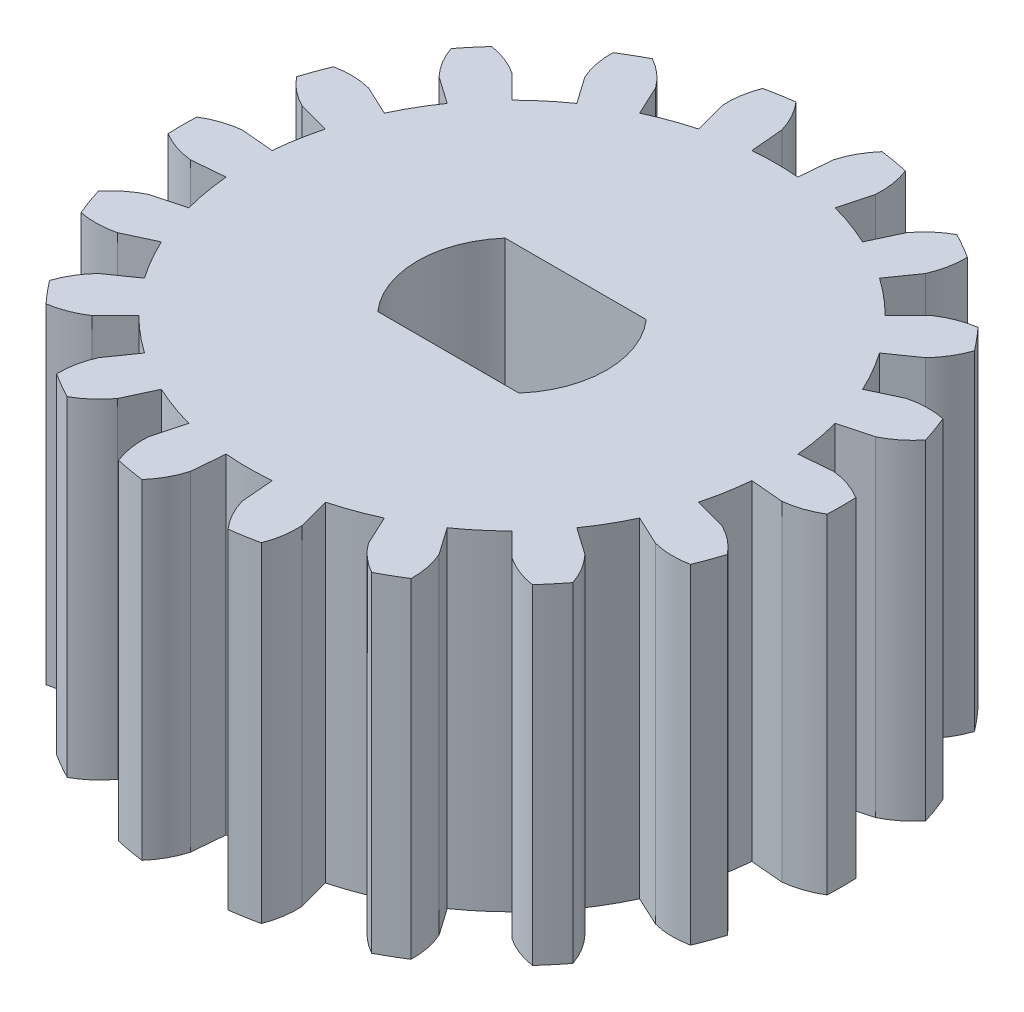
SolidWorks part; units mm, degrees
ref_plane "Front Plane" through (0, 0, 0) normal (0, 0, 1) x (1, 0, 0)
ref_plane "Top Plane" through (0, 0, 0) normal (0, 1, 0) x (1, 0, 0)
ref_plane "Right Plane" through (0, 0, 0) normal (1, 0, 0) x (0, 0, -1)
sketch "Sketch1" plane through (0, 0, 0) normal (0, 1, 0) x (1, 0, 0)
  line L0 (0, 0) -> (11.1857, 0) construction
  line L1 (0, 0) -> (12.0285, 2.121) construction
  line L2 (0, 0) -> (13.1752, 1.1527) construction
  line L3 (0, 0) -> (12.0271, 0.5251) construction
  line L4 (7.9696, 0.6972) -> (8.9658, 0.7844)
  line L5 (0, 0) -> (7.8785, 1.3892)
  line L6 (7.9696, -0.6972) -> (8.9658, -0.7844)
  line L7 (0, 0) -> (7.8785, -1.3892)
  circle A0 centre (0, 0) radius 10 construction
  circle A1 centre (0, 0) radius 9 construction
  circle A2 centre (0, 0) radius 8 construction
  arc A3 (7.9696, 0.6972) -> (7.8785, 1.3892) centre (0, 0) ccw
  arc A5 (9.9905, -0.4362) -> (9.9905, 0.4362) centre (0, 0) ccw
  arc A7 (7.9696, -0.6972) -> (7.8785, -1.3892) centre (0, 0) cw
  arc A8 (8.9658, -0.7844) -> (9.9905, -0.4362) centre (8.7033, 1.6699) ccw
  arc A9 (8.9658, 0.7844) -> (9.9905, 0.4362) centre (8.7033, -1.6699) cw
  dimension "D4" = 20
  dimension "D5" = 1
  dimension "D6" = 1
  dimension "D1" = 10
  dimension "D2" = 5
  dimension "D3" = 2.5
extrude "Boss-Extrude1" add sketch "Sketch1" along normal blind 10
pattern_circular "CirPattern1" count 18 every 20 about axis through (0, 0, 0) along (0, 1, 0) of "Boss-Extrude1"
sketch "Sketch4" plane through (0, 0, 0) normal (0, -1, 0) x (1, 0, 0)
  line L0 (-2.01, -1.8) -> (2.01, -1.8)
  line L1 (-2.01, 1.8) -> (2.01, 1.8)
  line L2 (0, 0) -> (0, 1.8) construction
  line L3 (0, 0) -> (0, -1.8) construction
  arc A0 (2.01, -1.8) -> (2.01, 1.8) centre (-0.0025, 0) ccw
  arc A1 (-2.01, -1.8) -> (-2.01, 1.8) centre (0.0025, 0) cw
  point P4 (0, -1.8)
  point P6 (0, 1.8)
  dimension "D3" = 2.7
  dimension "D4" = 2.7
  dimension "D1" = 4.02
  dimension "D2" = 1.8
sketch "Sketch6" plane through (0, 0, 0) normal (0, -1, 0) x (1, 0, 0)
  line L0 (-2.14, 1.93) -> (2.14, 1.93)
  line L1 (-2.14, -1.93) -> (2.14, -1.93)
  line L2 (-2.14, -1.93) -> (-2.01, -1.8) construction
  line L3 (2.01, -1.8) -> (2.14, -1.93) construction
  line L4 (2.01, 1.8) -> (2.14, 1.93) construction
  line L5 (-2.01, 1.8) -> (-2.14, 1.93) construction
  line L6 (2.14, 1.93) -> (2.14, 1.8) construction
  line L7 (2.14, 1.8) -> (2.01, 1.8) construction
  line L8 (2.01, -1.8) -> (2.14, -1.8) construction
  line L9 (2.14, -1.8) -> (2.14, -1.93) construction
  line L10 (-2.01, 1.8) -> (2.01, 1.8) construction
  arc A0 (2.14, 1.93) -> (2.14, -1.93) centre (-0.0525, 0) cw
  arc A1 (-2.14, -1.93) -> (-2.14, 1.93) centre (0.0525, 0) cw
  arc A2 (2.01, -1.8) -> (2.01, 1.8) centre (-0.0025, 0) ccw construction
  dimension "D2" = 0.05
  dimension "D1" = 0.13
extrude "Cut-Extrude1" cut sketch "Sketch6" against normal through all
sketch "Sketch5" plane through (0, 0, 0) normal (0, -1, 0) x (1, 0, 0)
  line L0 (-2.5142, 2.3999) -> (1.5058, 2.3999)
  line L1 (-2.5142, -2.3999) -> (1.5058, -2.3999)
  line L3 (0, 1.8) -> (0, 2.3999) construction
  line L4 (0, -1.8) -> (0, -2.3999) construction
  line L5 (-2.01, -1.8) -> (2.01, -1.8) construction
  line L6 (-2.5142, 2.3999) -> (-2.01, 1.8) construction
  line L7 (1.5058, 2.3999) -> (2.01, 1.8) construction
  line L8 (1.5058, -2.3999) -> (2.01, -1.8) construction
  line L9 (-2.5142, -2.3999) -> (-2.01, -1.8) construction
sketch "Sketch2" plane through (0, 0, 0) normal (0, -1, 0) x (1, 0, 0)
  line L1 (2.3094, -4) -> (4.6188, 0)
  line L2 (4.6188, 0) -> (2.3094, 4)
  line L3 (2.3094, 4) -> (-2.3094, 4)
  line L4 (-2.3094, 4) -> (-4.6188, 0)
  line L5 (-4.6188, 0) -> (-2.3094, -4)
  line L6 (-2.3094, -4) -> (2.3094, -4)
  circle A0 centre (0, 0) radius 4 construction
  dimension "D1" = 8
